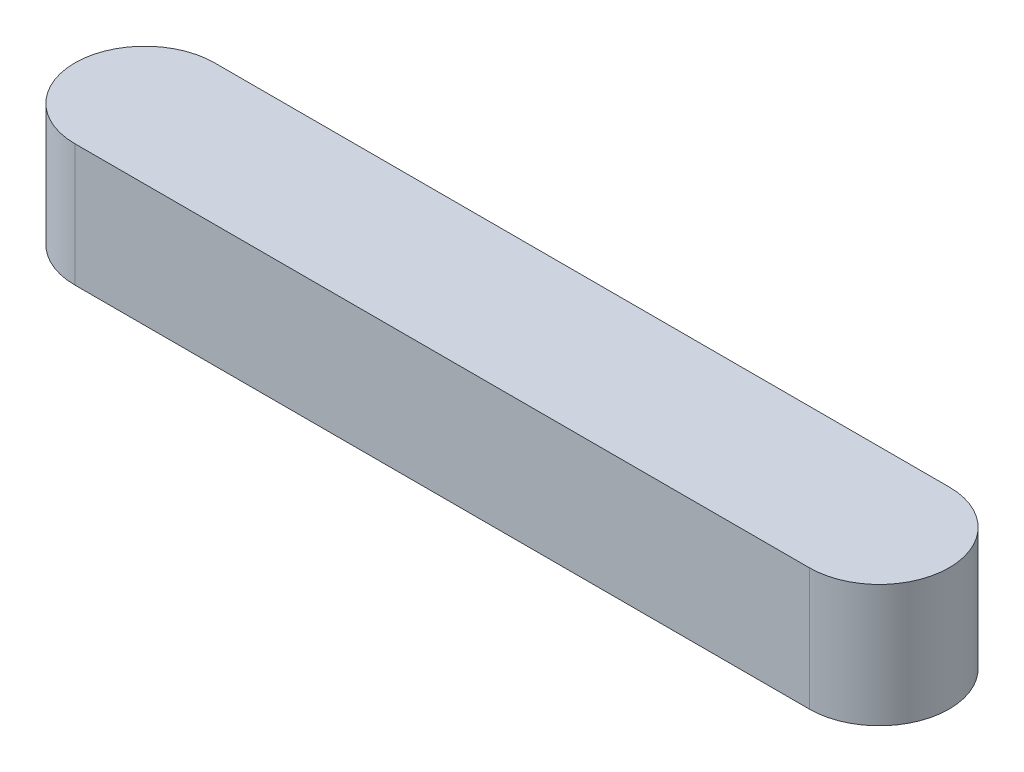
SolidWorks part; units mm, degrees
ref_plane "Спереди" through (0, 0, 0) normal (0, 0, 1) x (1, 0, 0)
ref_plane "Сверху" through (0, 0, 0) normal (0, 1, 0) x (1, 0, 0)
ref_plane "Справа" through (0, 0, 0) normal (1, 0, 0) x (0, 0, -1)
sketch "Эскиз1" plane through (0, 0, 0) normal (0, 1, 0) x (1, 0, 0)
  line L0 (0, 0) -> (42, 0) construction
  line L2 (0, 4) -> (42, 4)
  line L3 (0, -4) -> (42, -4)
  arc A0 (0, 4) -> (0, -4) centre (0, 0) ccw
  arc A1 (42, -4) -> (42, 4) centre (42, 0) ccw
  point P5 (21, 0)
extrude "Бобышка-Вытянуть1" add sketch "Эскиз1" along normal blind 7
